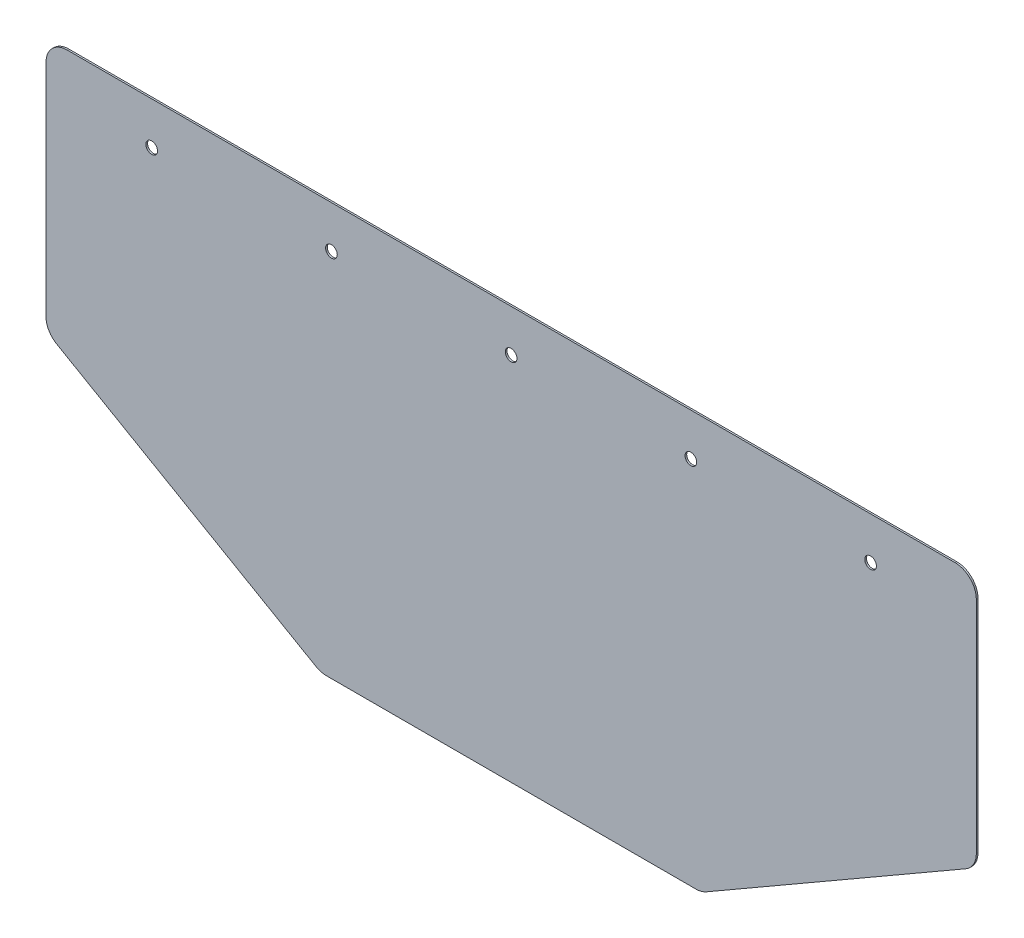
SolidWorks part; units mm, degrees
material "5052-H32"
ref_plane "Plan de face" through (0, 0, 0) normal (0, 0, 1) x (1, 0, 0)
ref_plane "Plan de dessus" through (0, 0, 0) normal (0, 1, 0) x (1, 0, 0)
ref_plane "Plan de droite" through (0, 0, 0) normal (1, 0, 0) x (0, 0, -1)
sketch "Sketch2" plane through (0, 0, 0) normal (0, 0, 1) x (1, 0, 0)
  line L0 (285.6206, 115.5309) -> (-273.1794, 115.5309)
  line L1 (-273.1794, 115.5309) -> (-273.1794, -29.5341)
  line L2 (6.2206, 115.5309) -> (6.2206, -132.1191) construction
  line L3 (-266.8259, -40.5346) -> (-111.0251, -130.4197)
  line L4 (6.2206, -132.1191) -> (-104.6786, -132.1191)
  line L5 (285.6206, 115.5309) -> (285.6206, -29.5341)
  line L6 (6.2206, -132.1191) -> (117.1198, -132.1191)
  line L7 (279.2671, -40.5346) -> (123.4663, -130.4197)
  circle A0 centre (-209.6794, 90.1309) radius 3.5
  circle A1 centre (-101.7294, 90.1309) radius 3.5
  circle A2 centre (6.2206, 90.1309) radius 3.5
  circle A3 centre (114.1706, 90.1309) radius 3.5
  circle A4 centre (222.1206, 90.1309) radius 3.5
  arc A5 (-273.1794, -29.5341) -> (-266.8259, -40.5346) centre (-260.4794, -29.5341) ccw
  arc A6 (-104.6786, -132.1191) -> (-111.0251, -130.4197) centre (-104.6786, -119.4191) cw
  arc A7 (123.4663, -130.4197) -> (117.1198, -132.1191) centre (117.1198, -119.4191) cw
  arc A8 (285.6206, -29.5341) -> (279.2671, -40.5346) centre (272.9206, -29.5341) cw
extrude "Boss-Extrude1" add sketch "Sketch2" along normal blind 1.016
fillet "Fillet1" radius 12.7 2 edges at (285.6206, 115.5309, 0.508) (-273.1794, 115.5309, 0.508)
